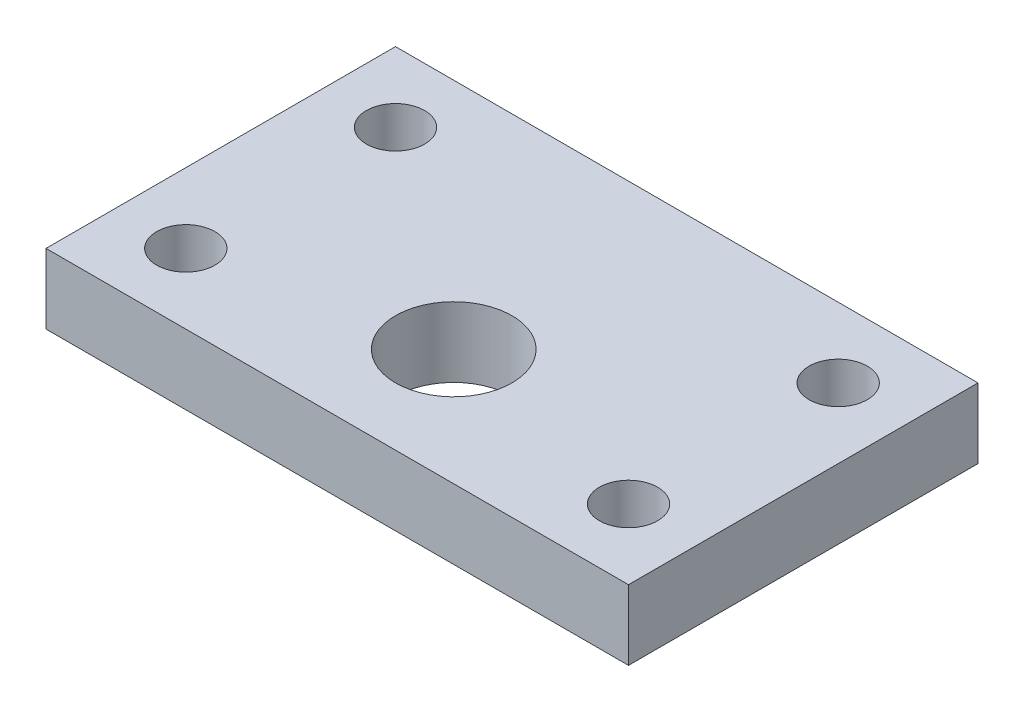
SolidWorks part; units mm, degrees
ref_plane "Front Plane" through (0, 0, 0) normal (0, 0, 1) x (1, 0, 0)
ref_plane "Top Plane" through (0, 0, 0) normal (0, 1, 0) x (1, 0, 0)
ref_plane "Right Plane" through (0, 0, 0) normal (1, 0, 0) x (0, 0, -1)
sketch "Sketch1" plane through (0, 0, 0) normal (0, 1, 0) x (1, 0, 0)
  line L1 (-125, 75) -> (125, 75)
  line L2 (-125, 75) -> (-125, -75)
  line L3 (-125, -75) -> (125, -75)
  line L4 (125, 75) -> (125, -75)
  line L5 (-125, 75) -> (125, -75) construction
  line L6 (-125, -75) -> (125, 75) construction
  circle A0 centre (0, -25) radius 25
  circle A1 centre (-95, -45) radius 12.5
  circle A2 centre (-95, 45) radius 12.5
  circle A3 centre (95, 45) radius 12.5
  circle A4 centre (95, -45) radius 12.5
  point P0 (0, 0)
  point P16 (0, 0)
  point P17 (0, 0)
  point P18 (0, 0)
  point P19 (0, 0)
  point P20 (0, 0)
  point P21 (85.833, -51.4998)
  point P22 (0, 0)
  point P23 (0, 0)
  point P24 (0, 0)
  dimension "D4" = 50
  dimension "D5" = 25
  dimension "D1" = 250
  dimension "D2" = 150
  dimension "D3" = 50
  dimension "D6" = 190
  dimension "D7" = 30
  dimension "D8" = 30
  dimension "D9" = 30
extrude "Boss-Extrude1" add sketch "Sketch1" along normal blind 30
